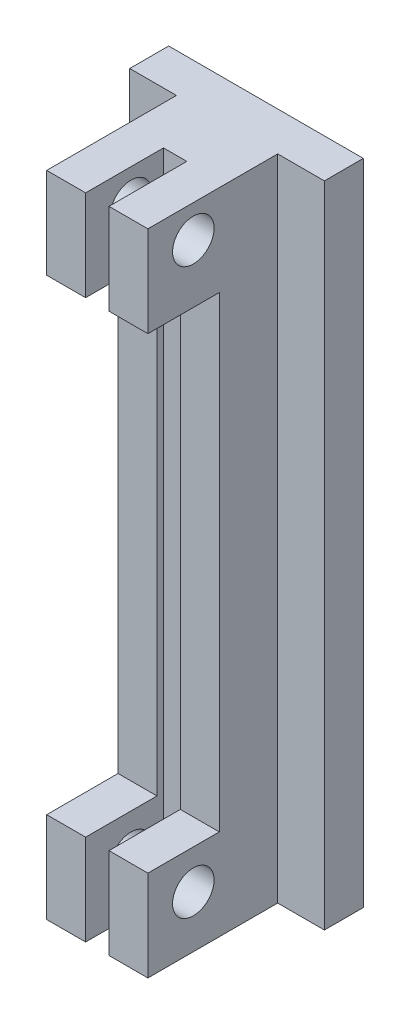
SolidWorks part; units mm, degrees
ref_plane "Front Plane" through (0, 0, 0) normal (0, 0, 1) x (1, 0, 0)
ref_plane "Top Plane" through (0, 0, 0) normal (0, 1, 0) x (1, 0, 0)
ref_plane "Right Plane" through (0, 0, 0) normal (1, 0, 0) x (0, 0, -1)
sketch "Sketch1" plane through (0, 0, 0) normal (0, 1, 0) x (1, 0, 0)
  line L0 (7.5, 0) -> (-7.5, 0)
  line L1 (-7.5, 0) -> (-7.5, -3)
  line L2 (-7.5, -3) -> (-3.9, -3)
  line L3 (-3.9, -3) -> (-3.9, -13)
  line L4 (-3.9, -13) -> (-0.9, -13)
  line L5 (-0.9, -13) -> (-0.9, -7)
  line L6 (-0.9, -7) -> (0.9, -7)
  line L7 (0.9, -7) -> (0.9, -13)
  line L8 (0.9, -13) -> (3.9, -13)
  line L9 (3.9, -13) -> (3.9, -3)
  line L10 (3.9, -3) -> (7.5, -3)
  line L11 (7.5, -3) -> (7.5, 0)
  point P0 (-5, -2.1867)
  point P4 (0, 0)
  dimension "D1" = 15
  dimension "D2" = 1.8
  dimension "D3" = 3
  dimension "D4" = 3
  dimension "D5" = 10
  dimension "D6" = 6
extrude "Boss-Extrude1" add sketch "Sketch1" along normal mid plane 50
sketch "Sketch2" plane through (-3.9, 0, 0) normal (-1, 0, 0) x (0, 0, 1)
  line L0 (13, 25) -> (13, -25) construction
  line L1 (13, -18) -> (7.5, -18)
  line L2 (13, -18) -> (13, 18)
  line L3 (13, 18) -> (7.5, 18)
  line L4 (7.5, -18) -> (7.5, 18)
  line L5 (3, -25) -> (13, -25) construction
  point P6 (9, -7.3502)
  point P7 (13, 0)
  point P8 (13, 0)
  dimension "D1" = 5.5
  dimension "D2" = 7
extrude "Cut-Extrude1" cut sketch "Sketch2" against normal through all
sketch "Sketch3" plane through (-3.9, 0, 0) normal (-1, 0, 0) x (0, 0, 1)
  line L0 (9.5, 22.5) -> (9.5, -21) construction
  line L1 (7, 25) -> (7, -25) construction
  line L2 (7, 25) -> (7, -25) construction
  line L3 (3, 25) -> (13, 25) construction
  circle A0 centre (9.5, 22.5) radius 1.6
  circle A1 centre (9.5, -21) radius 1.6
  point P4 (0, 0)
  point P7 (9.5, 0.75)
  dimension "D3" = 3.2
  dimension "D1" = 43.5
  dimension "D2" = 2.5
  dimension "D4" = 2.5
extrude "Cut-Extrude2" cut sketch "Sketch3" against normal through all
